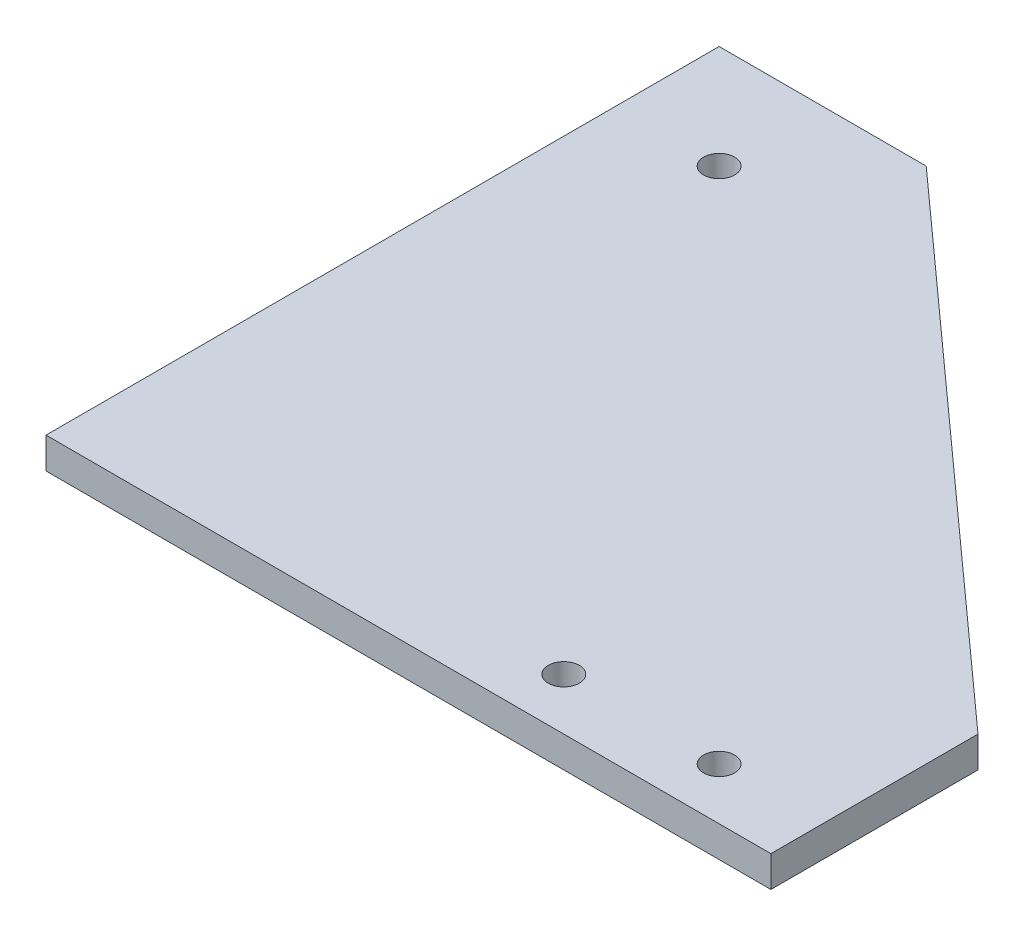
SolidWorks part; units mm, degrees
ref_plane "Plan de face" through (0, 0, 0) normal (0, 0, 1) x (1, 0, 0)
ref_plane "Plan de dessus" through (0, 0, 0) normal (0, 1, 0) x (1, 0, 0)
ref_plane "Plan de droite" through (0, 0, 0) normal (1, 0, 0) x (0, 0, -1)
sketch "Sketch1" plane through (0, 0, 0) normal (0, 1, 0) x (1, 0, 0)
  line L1 (35.5792, -33.0378) -> (-34.4208, -33.0378)
  line L2 (35.5792, -33.0378) -> (35.5792, -13.0378)
  line L3 (-14.4208, 31.9622) -> (-34.4208, 31.9622)
  line L4 (-34.4208, -33.0378) -> (-34.4208, 31.9622)
  line L5 (35.5792, -33.0378) -> (-34.4208, 31.9622) construction
  line L6 (10.2071, 9.797) -> (-34.4208, -33.0378) construction
  line L7 (-14.4208, 31.9622) -> (35.5792, -13.0378)
  circle A1 centre (25.5792, -28.0378) radius 1.5
  point P0 (0, 0)
  dimension "D4" = 10
  dimension "D1" = 70
  dimension "D2" = 65
  dimension "D3" = 20
  dimension "D5" = 20
  dimension "D7" = 5
extrude "Boss-Extrude1" add sketch "Sketch1" along normal blind 3
sketch "Sketch4" plane through (0, 3, 0) normal (0, 1, 0) x (-1, 0, 0)
  line L0 (-35.5792, 33.0378) -> (-35.5792, 13.0378) construction
  line L1 (34.4208, 33.0378) -> (-35.5792, 33.0378) construction
  circle A0 centre (-10.5792, 28.0378) radius 1.5
  dimension "D1" = 25
  dimension "D2" = 5
extrude "Cut-Extrude1" cut sketch "Sketch4" against normal blind 5
sketch "Sketch5" plane through (0, 3, 0) normal (0, 1, 0) x (-1, 0, 0)
  line L0 (34.4208, -31.9622) -> (34.4208, 33.0378) construction
  line L1 (14.4208, -31.9622) -> (34.4208, -31.9622) construction
  circle A0 centre (24.4208, -21.9622) radius 1.5
  dimension "D1" = 10
  dimension "D3" = 3
  dimension "D2" = 10
extrude "Cut-Extrude2" cut sketch "Sketch5" against normal through all
